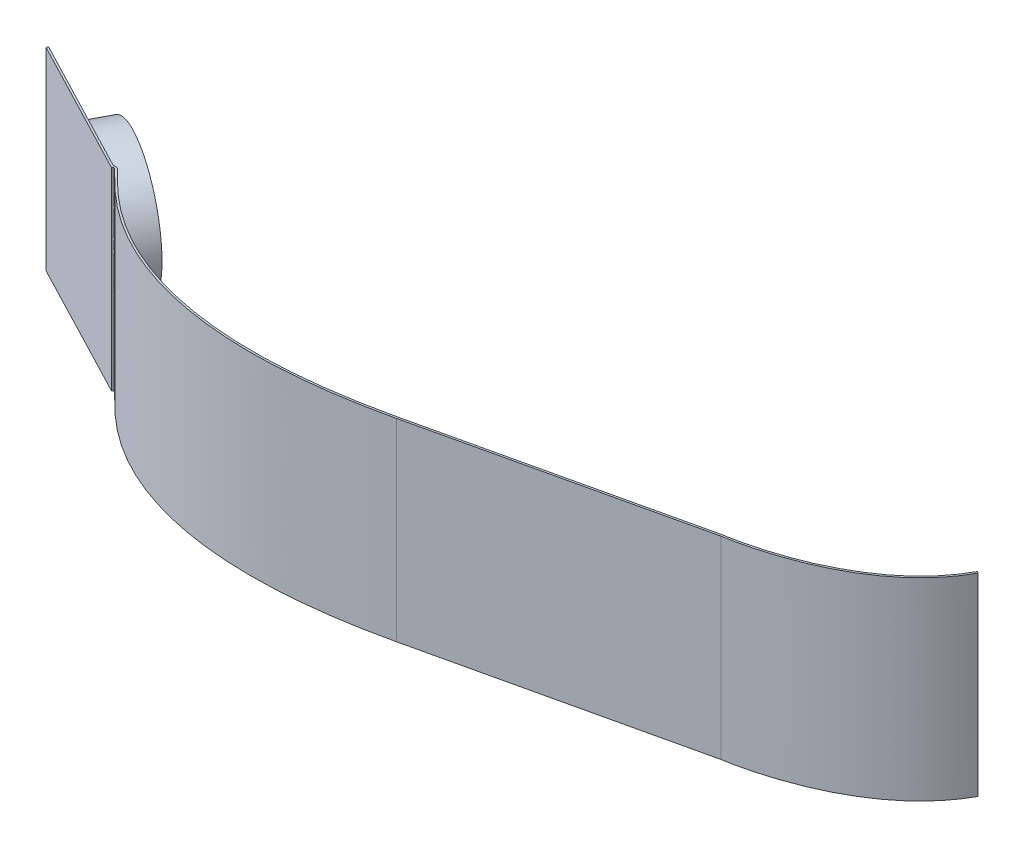
SolidWorks part; units mm, degrees
ref_plane "Front Plane" through (0, 0, 0) normal (0, 0, 1) x (1, 0, 0)
ref_plane "Top Plane" through (0, 0, 0) normal (0, 1, 0) x (1, 0, 0)
ref_plane "Right Plane" through (0, 0, 0) normal (1, 0, 0) x (0, 0, -1)
sketch "Sketch3" plane through (0, 0, 0) normal (0, 1, 0) x (1, 0, 0)
  line L0 (-8.2952, -4.9896) -> (-21.9441, -8.1051)
  line L1 (-40.5291, -4.2516) -> (-47.6231, -0.5537)
  line L2 (-8.3158, -4.8917) -> (-21.9664, -8.0076)
  line L3 (-40.5721, -4.1164) -> (-47.5769, -0.465)
  line L4 (-47.5769, -0.465) -> (-47.6231, -0.5537)
  line L5 (-0.088, 0.0475) -> (0, 0)
  spline S0 degree 3 poles (0, 0) (-2.2397, -4.1522) (-8.2975, -4.9871) (-8.2952, -4.9896) knots 0 0 0 0 1 1 1 1
  spline S1 degree 3 poles (-21.9441, -8.1051) (-36.5994, -11.4502) (-40.464, -3.3909) (-40.5291, -4.2516) knots 0 0 0 0 1 1 1 1
  spline S2 degree 1 poles (-0.088, 0.0475) (-8.3158, -4.8917) knots 0 0 1 1 construction
  spline S3 degree 1 poles (-21.9664, -8.0076) (-40.5721, -4.1164) knots 0 0 1 1 construction
  spline S4 degree 3 poles (-0.088, 0.0475) (-0.3564, -0.4501) (-1.0328, -1.3862) (-2.6834, -2.8506) (-4.5977, -3.8345) (-6.3084, -4.4303) (-7.1973, -4.6665) (-7.7443, -4.7881) (-8.0539, -4.8482) (-8.2656, -4.8847) (-8.2895, -4.8861) (-8.3158, -4.8917) knots 0 0 0 0 0.124589 0.249177 0.498355 0.622944 0.747532 0.809827 0.872121 0.934415 0.99671 0.99671 0.99671 0.99671
  spline S5 degree 3 poles (-21.9664, -8.0076) (-22.3961, -8.1056) (-23.2753, -8.2901) (-24.915, -8.571) (-26.8368, -8.7867) (-28.9188, -8.8491) (-31.4188, -8.7086) (-34.0451, -8.1799) (-36.4759, -7.1952) (-38.2616, -6.0735) (-39.2739, -5.2012) (-39.8372, -4.6471) (-40.1432, -4.3267) (-40.3232, -4.1658) (-40.4157, -4.0865) (-40.5362, -4.087) (-40.5721, -4.1164) knots 0 0 0 0 0.030179 0.060359 0.120718 0.181077 0.241436 0.362154 0.482872 0.60359 0.724308 0.784667 0.845026 0.905385 0.935564 0.965744 0.965744 0.965744 0.965744
  point P1 (-6.5394, -0.078)
  point P5 (-18.6579, 11.7461)
  point P6 (-7.6145, -0.3568)
  point P13 (-21.9205, 25.8097)
  point P14 (-26.1404, 18.9769)
  point P15 (-28.6025, 17.8189)
  point P16 (-39.0689, 24.2107)
  point P17 (-8.169, -1.1177)
  point P18 (-38.189, 18.3741)
  point P19 (-8.362, 0.4842)
  point P20 (-37.3478, 19.8269)
  point P22 (-8.0284, 2.365)
  point P23 (-8.5337, 0.6204)
  point P24 (-9.0369, -1.1999)
  point P25 (-8.7065, -3.5406)
  point P26 (-21.8733, 0.7671)
  point P27 (-21.4636, -1.7628)
  point P28 (-38.5504, 7.7159)
  point P29 (0, 0)
  point P30 (0, 0)
  point P31 (-40.1545, 4.7579)
  point P32 (-21.9441, -8.1051)
  point P33 (0, 0)
  point P34 (-43.8934, 5.5597)
  point P35 (-40.3197, -3.4164)
  point P36 (-46.8977, 0.6149)
  point P37 (-47.1437, 0)
  point P38 (-40.6184, -4.2051)
  dimension "D2" = 10
  dimension "D3" = 20
  dimension "D1" = 14
  dimension "D4" = 8
  dimension "D5" = 0.1
extrude "Boss-Extrude1" add sketch "Sketch3" along normal blind 10
sketch "Sketch4" plane through (-10.3564, 0, 19.8673) normal (0.4622, 0, -0.8868) x (-0.8868, 0, -0.4622)
  line L0 (34.0746, 0) -> (41.9739, 10) construction
  circle A0 centre (38.0243, 5) radius 3.5
extrude "Boss-Extrude2" add sketch "Sketch4" along normal blind 2
